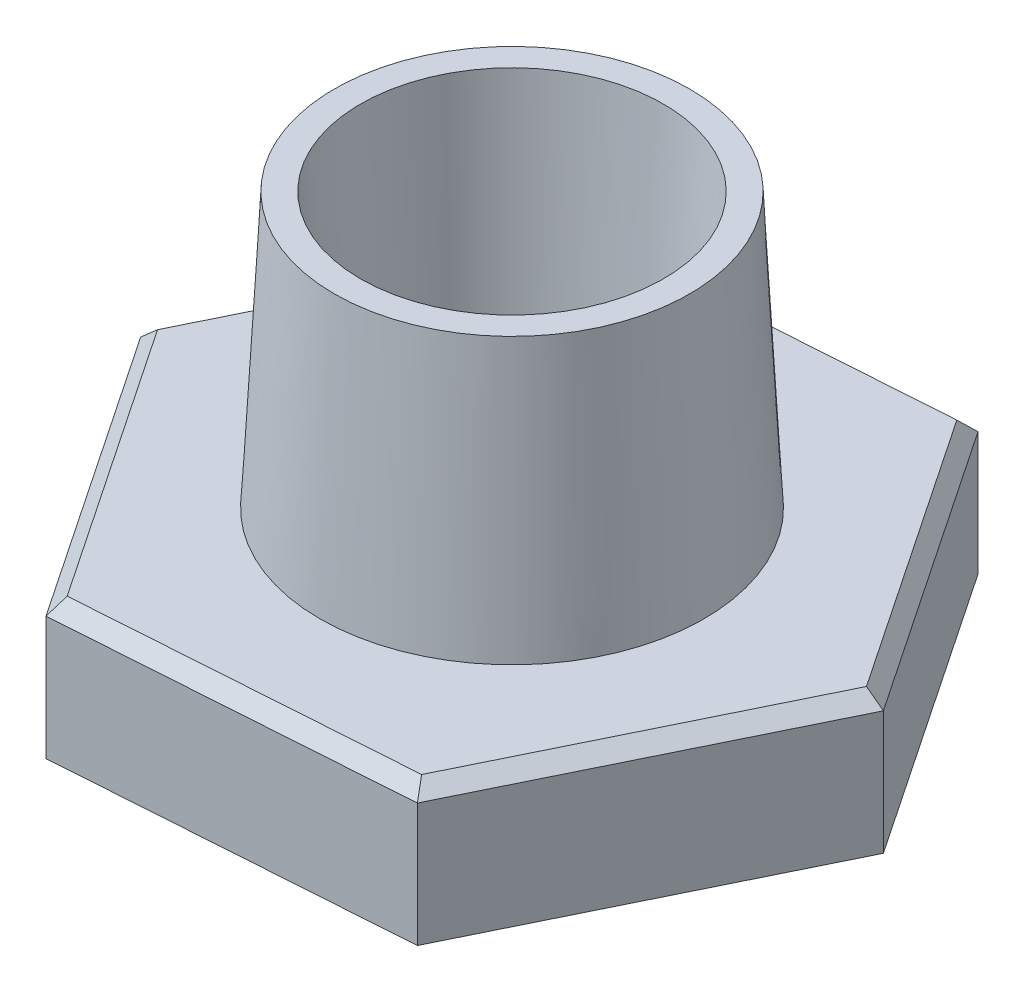
SolidWorks part; units mm, degrees
ref_plane "Front Plane" through (0, 0, 0) normal (0, 0, 1) x (1, 0, 0)
ref_plane "Top Plane" through (0, 0, 0) normal (0, 1, 0) x (1, 0, 0)
ref_plane "Right Plane" through (0, 0, 0) normal (1, 0, 0) x (0, 0, -1)
sketch "Sketch1" plane through (0, 0, 0) normal (0, 1, 0) x (1, 0, 0)
  line L1 (7.0886, -10.5397) -> (12.6719, 0.8691)
  line L2 (12.6719, 0.8691) -> (5.5833, 11.4088)
  line L3 (5.5833, 11.4088) -> (-7.0886, 10.5397)
  line L4 (-7.0886, 10.5397) -> (-12.6719, -0.8691)
  line L5 (-12.6719, -0.8691) -> (-5.5833, -11.4088)
  line L6 (-5.5833, -11.4088) -> (7.0886, -10.5397)
  circle A0 centre (0, 0) radius 11 construction
  circle A1 centre (0, 0) radius 5
extrude "Boss-Extrude1" add sketch "Sketch1" along normal blind 5
chamfer "Chamfer1" distance 0.5 angle 45 6 edges at (-9.1276, 5, 6.1389) (-9.8803, 5, -4.8353) (-0.7527, 5, -10.9742) (9.1276, 5, -6.1389) (9.8803, 5, 4.8353) (0.7527, 5, 10.9742)
sketch "Sketch2" plane through (0, 5, 0) normal (0, 1, 0) x (1, 0, 0)
  circle A0 centre (0, 0) radius 7
  circle A1 centre (0, 0) radius 5
extrude "Boss-Extrude2" add sketch "Sketch2" along normal blind 10 draft 3
